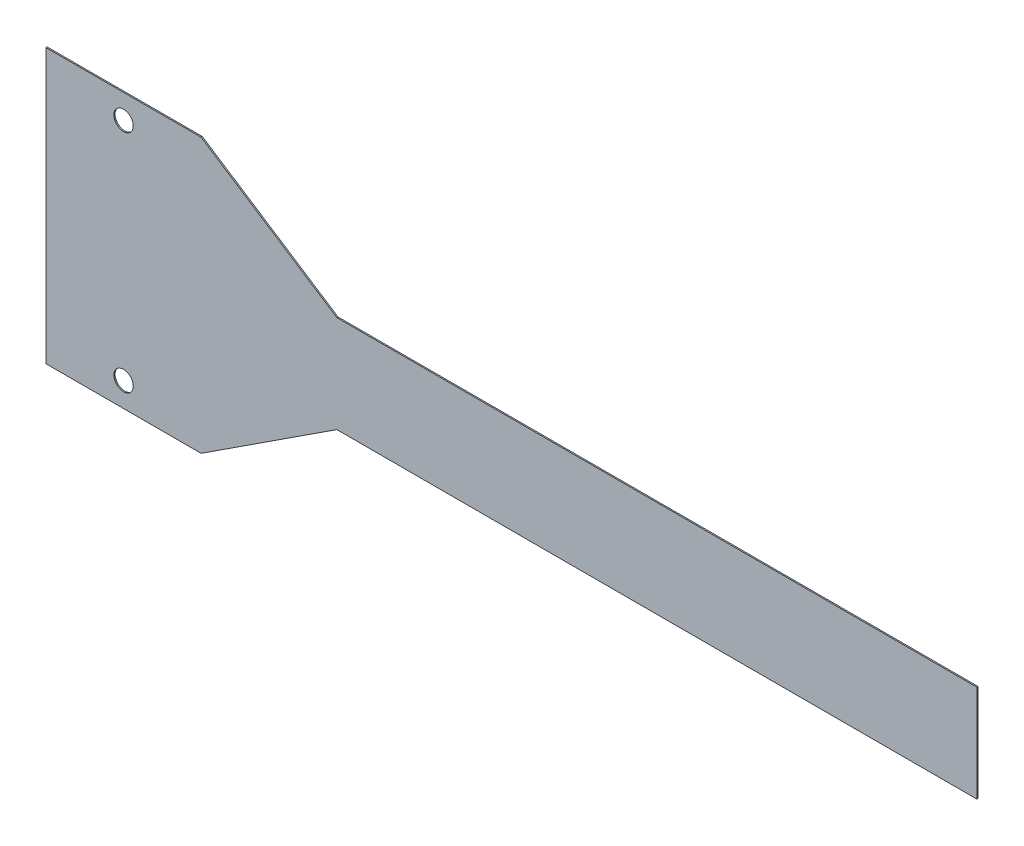
SolidWorks part; units mm, degrees
ref_plane "Front Plane" through (0, 0, 0) normal (0, 0, 1) x (1, 0, 0)
ref_plane "Top Plane" through (0, 0, 0) normal (0, 1, 0) x (1, 0, 0)
ref_plane "Right Plane" through (0, 0, 0) normal (1, 0, 0) x (0, 0, -1)
sketch "Sketch1" plane through (0, 0, 0) normal (0, 0, 1) x (1, 0, 0)
  line L0 (0, -9.12) -> (16, -9.12)
  line L1 (16, -9.12) -> (30, 0)
  line L2 (30, 0) -> (96, 0)
  line L3 (96, 0) -> (96, 10)
  line L4 (96, 10) -> (30, 10)
  line L5 (30, 10) -> (16, 19.12)
  line L6 (16, 19.12) -> (0, 19.12)
  line L7 (0, 19.12) -> (0, -9.12)
  circle A0 centre (8, -6.62) radius 1
  circle A1 centre (8, 16.62) radius 1
  dimension "D6" = 2
  dimension "D8" = 2
  dimension "D1" = 10
  dimension "D2" = 96
  dimension "D3" = 28.24
  dimension "D4" = 16
  dimension "D5" = 66
  dimension "D7" = 8
  dimension "D9" = 8
  dimension "D10" = 2.5
  dimension "D11" = 23.24
extrude "Boss-Extrude1" add sketch "Sketch1" along normal blind 0.125
sketch "Sketch2" plane through (0, 0, 0) normal (0, 0, 1) x (1, 0, 0)
  line L0 (5, -4.12) -> (5, -1.12)
  line L1 (5, -1.12) -> (11, -1.12)
  line L2 (11, -1.12) -> (11, -2.12)
  line L3 (11, -2.12) -> (30, 1.5)
  line L4 (30, 1.5) -> (86, 1.5)
  line L5 (86, 1.5) -> (86, 4.5)
  line L6 (86, 4.5) -> (86, 5.5)
  line L7 (86, 5.5) -> (87, 5.5)
  line L8 (87, 5.5) -> (93, 5.5)
  line L9 (93, 5.5) -> (93, 4.5)
  line L10 (93, 4.5) -> (87, 4.5)
  line L11 (87, 4.5) -> (87, 1.5)
  line L12 (87, 1.5) -> (87, 0.5)
  line L13 (87, 0.5) -> (86, 0.5)
  line L14 (86, 0.5) -> (30, 0.5)
  line L15 (30, 0.5) -> (11, -3.12)
  line L16 (11, -3.12) -> (11, -4.12)
  line L17 (11, -4.12) -> (5, -4.12)
  line L18 (5, 0.96) -> (5, 3.96)
  line L19 (5, 3.96) -> (11, 3.96)
  line L20 (11, 3.96) -> (11, 2.96)
  line L21 (11, 2.96) -> (30, 3.5)
  line L22 (30, 3.5) -> (68.5, 3.5)
  line L23 (68.5, 3.5) -> (68.5, 4.5)
  line L24 (68.5, 4.5) -> (68.5, 5.5)
  line L25 (68.5, 5.5) -> (69.5, 5.5)
  line L26 (69.5, 5.5) -> (75.5, 5.5)
  line L27 (75.5, 5.5) -> (75.5, 4.5)
  line L28 (75.5, 4.5) -> (69.5, 4.5)
  line L29 (69.5, 4.5) -> (69.5, 3.5)
  line L30 (69.5, 3.5) -> (69.5, 2.5)
  line L31 (69.5, 2.5) -> (68.5, 2.5)
  line L32 (68.5, 2.5) -> (30, 2.5)
  line L33 (30, 2.5) -> (11, 1.96)
  line L34 (11, 1.96) -> (11, 0.96)
  line L35 (11, 0.96) -> (5, 0.96)
  line L36 (94.5, 6.5) -> (93.5, 6.5)
  line L37 (93.5, 6.5) -> (30, 6.5)
  line L38 (30, 6.5) -> (11, 7.04)
  line L39 (11, 7.04) -> (11, 6.04)
  line L40 (11, 6.04) -> (5, 6.04)
  line L41 (5, 6.04) -> (5, 9.04)
  line L42 (5, 9.04) -> (11, 9.04)
  line L43 (11, 9.04) -> (11, 8.04)
  line L44 (11, 8.04) -> (30, 7.5)
  line L45 (30, 7.5) -> (93.5, 7.5)
  line L46 (93.5, 7.5) -> (93.5, 8.3)
  line L47 (93.5, 8.3) -> (30, 8.3)
  line L48 (30, 8.3) -> (11, 12.12)
  line L49 (11, 12.12) -> (11, 11.12)
  line L50 (11, 11.12) -> (5, 11.12)
  line L51 (5, 11.12) -> (5, 14.12)
  line L52 (5, 14.12) -> (11, 14.12)
  line L53 (11, 14.12) -> (11, 13.12)
  line L54 (11, 13.12) -> (30, 9.3)
  line L55 (30, 9.3) -> (93.5, 9.3)
  line L56 (93.5, 9.3) -> (94.5, 9.3)
  line L57 (94.5, 9.3) -> (94.5, 8.3)
  line L58 (94.5, 8.3) -> (94.5, 7.5)
  line L59 (94.5, 7.5) -> (94.5, 6.5)
extrude "Boss-Extrude2" add sketch "Sketch2" against normal blind 0.02 separate body
